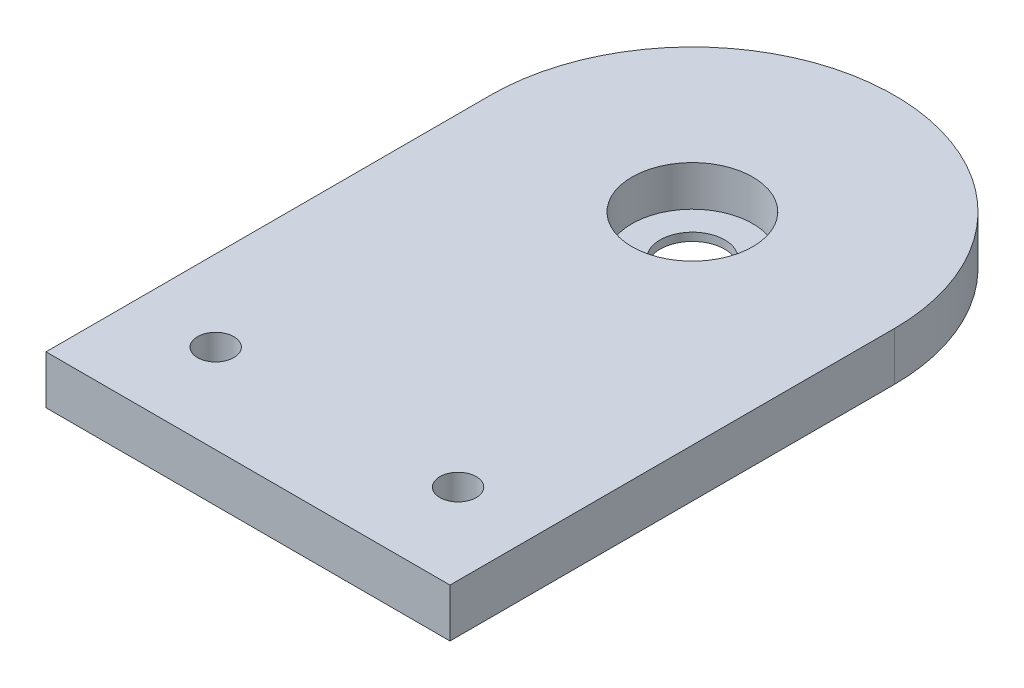
SolidWorks part; units mm, degrees
material "Aleación 6061"
ref_plane "Alzado" through (0, 0, 0) normal (0, 0, 1) x (1, 0, 0)
ref_plane "Planta" through (0, 0, 0) normal (0, 1, 0) x (1, 0, 0)
ref_plane "Vista lateral" through (0, 0, 0) normal (1, 0, 0) x (0, 0, -1)
sketch "Sk_Placa" plane through (0, 0, 0) normal (0, 1, 0) x (1, 0, 0)
  line L1 (-25, -526) -> (25, -526)
  line L2 (-25, -526) -> (-25, -490)
  line L3 (-25, -490) -> (25, -490)
  line L4 (25, -526) -> (25, -490)
  line L5 (-25, -526) -> (25, -490) construction
  line L6 (-25, -490) -> (25, -526) construction
  point P0 (0, -508)
  dimension "D1" = 50
  dimension "D2" = 36
  dimension "D3" = 508
extrude "Placa" add sketch "Sk_Placa" along normal blind 6 from offset 40.5
sketch "Sk_Extremo" plane through (0, 0, 0) normal (0, 1, 0) x (1, 0, 0)
  circle A0 centre (0, -490) radius 25
  dimension "D1" = 50
  dimension "D2" = 490
extrude "Extremo" add sketch "Sk_Extremo" along normal blind 6 from offset 40.5
sketch "Sk_Alojamiento_696ZZ" plane through (0, 0, 0) normal (0, 1, 0) x (1, 0, 0)
  circle A0 centre (0, -490) radius 7.475
  dimension "D1" = 14.95
  dimension "D2" = 490
extrude "Alojamiento_696ZZ" cut sketch "Sk_Alojamiento_696ZZ" along normal blind 5 from offset 39.5
sketch "Sk_Paso_extractor" plane through (0, 0, 0) normal (0, 1, 0) x (1, 0, 0)
  circle A0 centre (0, -490) radius 4
  dimension "D1" = 8
  dimension "D2" = 490
extrude "Paso_extractor" cut sketch "Sk_Paso_extractor" along normal blind 1 from offset 40.5
sketch "Sk_Extension_pestanas" plane through (0, 0, 0) normal (0, 1, 0) x (1, 0, 0)
  line L1 (-25, -545) -> (25, -545)
  line L2 (-25, -545) -> (-25, -526)
  line L3 (-25, -526) -> (25, -526)
  line L4 (25, -545) -> (25, -526)
  line L5 (-25, -545) -> (25, -526) construction
  line L6 (-25, -526) -> (25, -545) construction
  point P0 (0, -535.5)
  dimension "D1" = 50
  dimension "D2" = 19
  dimension "D3" = 535.5
extrude "Extension_pestanas" add sketch "Sk_Extension_pestanas" along normal blind 6 from offset 40.5
sketch "Sk_Pasantes_M4_repisa" plane through (0, 0, 0) normal (0, 1, 0) x (1, 0, 0)
  circle A0 centre (-15, -534) radius 2.25
  circle A1 centre (15, -534) radius 2.25
  dimension "D1" = 4.5
  dimension "D4" = 4.5
  dimension "D2" = 15
  dimension "D3" = 534
  dimension "D5" = 15
  dimension "D6" = 534
extrude "Pasantes_M4_repisa" cut sketch "Sk_Pasantes_M4_repisa" along normal blind 6 from offset 40.5
